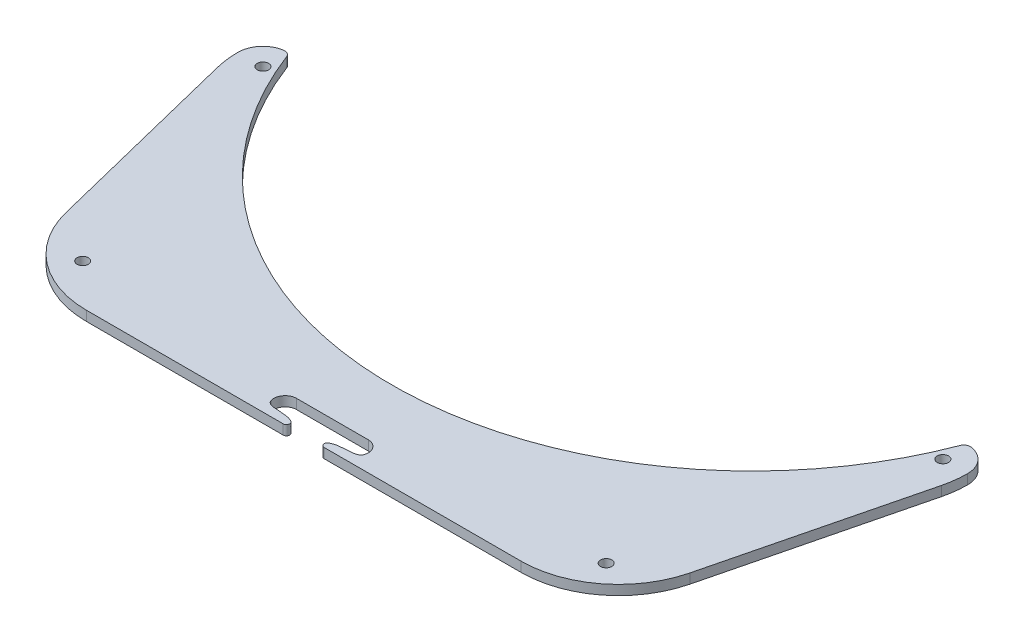
SolidWorks part; units mm, degrees
ref_plane "前视基准面" through (0, 0, 0) normal (0, 0, 1) x (1, 0, 0)
ref_plane "上视基准面" through (0, 0, 0) normal (0, 1, 0) x (1, 0, 0)
ref_plane "右视基准面" through (0, 0, 0) normal (1, 0, 0) x (0, 0, -1)
sketch "草图1" plane through (0, 0, 0) normal (0, 1, 0) x (1, 0, 0)
  line L3 (-66.7806, 154.594) -> (66.7806, 154.594)
  line L4 (-95.8987, 131.8145) -> (-111.2655, 69.8447)
  line L5 (-96.25, 148.3486) -> (-96.25, 83.3486) construction
  line L6 (95.8987, 131.8145) -> (111.2655, 69.8447)
  line L7 (95.8987, -6.5662) -> (111.2655, 55.4037)
  line L9 (-95.8987, -6.5662) -> (-111.2655, 55.4037)
  line L10 (137.9048, 62.6242) -> (-113.2043, 62.6242) construction
  line L12 (-66.7806, -29.3457) -> (66.7806, -29.3457)
  line L20 (0, 9.3997) -> (0, 129.3997) construction
  arc A0 (95.8987, -6.5662) -> (66.7806, -29.3457) centre (66.7806, 0.6543) cw
  arc A1 (-66.7806, -29.3457) -> (-95.8987, -6.5662) centre (-66.7806, 0.6543) cw
  arc A2 (111.2655, 55.4037) -> (111.2655, 69.8447) centre (82.1474, 62.6242) ccw
  arc A3 (-111.2655, 69.8447) -> (-111.2655, 55.4037) centre (-82.1474, 62.6242) ccw
  arc A6 (-66.7806, 154.594) -> (-95.8987, 131.8145) centre (-66.7806, 124.594) ccw
  arc A7 (95.8987, 131.8145) -> (66.7806, 154.594) centre (66.7806, 124.594) ccw
  point P16 (-90.25, 154.594)
  point P18 (90.25, -29.3457)
  point P24 (-90.25, -29.3457)
  point P26 (0, 62.6242)
  point P27 (90.25, 154.594)
  point P28 (113.2043, 62.6242)
  dimension "D5" = 30
  dimension "D6" = 30
extrude "凸台-拉伸1" add sketch "草图1" along normal blind 3
sketch "草图2" plane through (0, 0, 0) normal (0, -1, 0) x (1, 0, 0)
  line L12 (95.8987, -131.8145) -> (111.2655, -69.8447)
  line L13 (-66.7806, -154.594) -> (66.7806, -154.594)
  line L14 (-111.2655, -69.8447) -> (-95.8987, -131.8145)
  line L15 (-95.8987, 6.5662) -> (-111.2655, -55.4037)
  line L16 (66.7806, 29.3457) -> (-66.7806, 29.3457)
  line L17 (111.2655, -55.4037) -> (95.8987, 6.5662)
  line L18 (95.8987, -131.8145) -> (111.2655, -69.8447)
  line L19 (-66.7806, -154.594) -> (66.7806, -154.594)
  line L20 (-111.2655, -69.8447) -> (-95.8987, -131.8145)
  arc A14 (97.767, -56.3401) -> (-97.767, -56.3401) centre (0, -108.5017) ccw
  arc A15 (97.767, -56.3401) -> (111.4108, -56.0169) centre (104.5075, -52.7438) ccw
  arc A20 (-111.4108, -56.0169) -> (-97.767, -56.3401) centre (-104.5075, -52.7438) ccw
  arc A22 (66.7806, -154.594) -> (95.8987, -131.8145) centre (66.7806, -124.594) ccw
  arc A23 (-95.8987, -131.8145) -> (-66.7806, -154.594) centre (-66.7806, -124.594) ccw
  arc A24 (-111.2655, -55.4037) -> (-111.2655, -69.8447) centre (-82.1474, -62.6242) ccw
  arc A25 (-66.7806, 29.3457) -> (-95.8987, 6.5662) centre (-66.7806, -0.6543) ccw
  arc A26 (95.8987, 6.5662) -> (66.7806, 29.3457) centre (66.7806, -0.6543) ccw
  arc A27 (111.2655, -69.8447) -> (111.2655, -55.4037) centre (82.1474, -62.6242) ccw
  arc A28 (66.7806, -154.594) -> (95.8987, -131.8145) centre (66.7806, -124.594) ccw
  arc A29 (-95.8987, -131.8145) -> (-66.7806, -154.594) centre (-66.7806, -124.594) ccw
  arc A30 (-111.4108, -56.0169) -> (-111.2655, -69.8447) centre (-82.1474, -62.6242) ccw
  arc A33 (111.2655, -69.8447) -> (111.4108, -56.0169) centre (82.1474, -62.6242) ccw
  dimension "D2" = 0
extrude "切除-拉伸1" cut sketch "草图2" against normal blind 10
sketch "草图3" plane through (0, 3, 0) normal (0, 1, 0) x (1, 0, 0)
  line L0 (111.2655, 55.4037) -> (97.0472, 55.0128)
  line L1 (0, 27.3971) -> (0, 55.0128) construction
  line L2 (-111.2655, 55.4037) -> (-97.0472, 55.0128)
  arc A0 (112.1474, 62.6242) -> (97.767, 66.2204) centre (104.5075, 62.6242) ccw construction
  arc A1 (111.2655, 55.4037) -> (111.2655, 69.8447) centre (82.1474, 62.6242) ccw construction
  arc A2 (112.1474, 62.6242) -> (105.6711, 70.1749) centre (104.5075, 62.6242) ccw
  arc A3 (111.2655, 55.4037) -> (112.1474, 62.6242) centre (82.1474, 62.6242) ccw
  arc A4 (97.0472, 55.0128) -> (103.4985, 68.9128) centre (0, 108.5017) ccw
  arc A5 (105.6711, 70.1749) -> (103.4985, 68.9128) centre (105.3665, 68.1983) ccw
  arc A6 (-105.6711, 70.1749) -> (-103.4985, 68.9128) centre (-105.3665, 68.1983) cw
  arc A7 (-97.0472, 55.0128) -> (-103.4985, 68.9128) centre (0, 108.5017) cw
  arc A8 (-111.2655, 55.4037) -> (-112.1474, 62.6242) centre (-82.1474, 62.6242) cw
  arc A9 (-112.1474, 62.6242) -> (-105.6711, 70.1749) centre (-104.5075, 62.6242) cw
  dimension "D1" = 2
extrude "凸台-拉伸2" add sketch "草图3" against normal up to surface (3 mm away) up to face at (0, 0, -20.3416)
sketch "草图4" plane through (0, 3, 0) normal (0, 1, 0) x (1, 0, 0)
  circle A0 centre (104.5075, 62.6242) radius 1.75 construction
  circle A1 centre (104.5075, 62.6242) radius 1.75
  circle A2 centre (-104.5075, 62.6242) radius 1.75 construction
  circle A3 centre (-104.5075, 62.6242) radius 1.75
  circle A4 centre (80.4502, -16.819) radius 1.75 construction
  circle A5 centre (-80.4502, -16.819) radius 1.75 construction
  circle A6 centre (80.4502, -16.819) radius 1.75
  circle A7 centre (-80.4502, -16.819) radius 1.75
extrude "切除-拉伸2" cut sketch "草图4" against normal blind 10
sketch "草图5" plane through (0, 3, 0) normal (0, 1, 0) x (1, 0, 0)
  line L0 (11.0166, -20.5139) -> (-11.0166, -20.5139) construction
  line L1 (11.0166, -20.5139) -> (-11.0166, -20.5139)
  line L2 (6.2934, -29.3457) -> (-6.2934, -29.3457)
  arc A0 (-6.2934, -29.3457) -> (-5.8046, -27.4733) centre (-6.2934, -28.3457) ccw construction
  arc A1 (5.8046, -27.4733) -> (6.2934, -29.3457) centre (6.2934, -28.3457) ccw construction
  arc A2 (14.3785, -24.9877) -> (11.0166, -20.5139) centre (11.0166, -24.0139) ccw construction
  arc A3 (-11.0166, -20.5139) -> (-14.3785, -24.9877) centre (-11.0166, -24.0139) ccw construction
  arc A4 (-6.2934, -29.3457) -> (-5.8046, -27.4733) centre (-6.2934, -28.3457) ccw
  arc A5 (5.8046, -27.4733) -> (6.2934, -29.3457) centre (6.2934, -28.3457) ccw
  arc A6 (14.3785, -24.9877) -> (11.0166, -20.5139) centre (11.0166, -24.0139) ccw
  arc A7 (-11.0166, -20.5139) -> (-14.3785, -24.9877) centre (-11.0166, -24.0139) ccw
  spline S0 degree 3 poles (1568.8603, 1196.5676) (-54.9954, -7.884) (-20.7022, -27.744) (-2.2559, -25.9669) (5.5043, -43.2944) (-1844.0586, 760.3134) knots -2.871799 -2.871799 -2.871799 -2.871799 0.274124 0.74549 2.315213 2.315213 2.315213 2.315213 only from (-14.3785, -24.9877) to (-5.8046, -27.4733) construction
  spline S1 degree 3 poles (1844.0565, 760.3125) (-5.5043, -43.2944) (2.2559, -25.9669) (20.7021, -27.744) (54.9951, -7.8841) (-1568.8368, 1196.5502) knots -1.537819 -1.537819 -1.537819 -1.537819 0.031904 0.50327 3.649178 3.649178 3.649178 3.649178 only from (5.8046, -27.4733) to (14.3785, -24.9877) construction
  spline S2 degree 3 poles (-14.3785, -24.9877) (-14.0507, -26.1193) (-10.4893, -26.7601) (-7.7247, -26.4938) (-5.9045, -27.4173) (-5.8046, -27.4733) knots 0 0 0 0 0.274124 0.74549 0.777394 0.777394 0.777394 0.777394
  spline S3 degree 3 poles (5.8046, -27.4733) (5.9045, -27.4173) (7.7247, -26.4938) (10.4893, -26.7601) (14.0507, -26.1193) (14.3785, -24.9877) knots 0 0 0 0 0.031904 0.50327 0.777394 0.777394 0.777394 0.777394
extrude "切除-拉伸3" cut sketch "草图5" against normal blind 10
